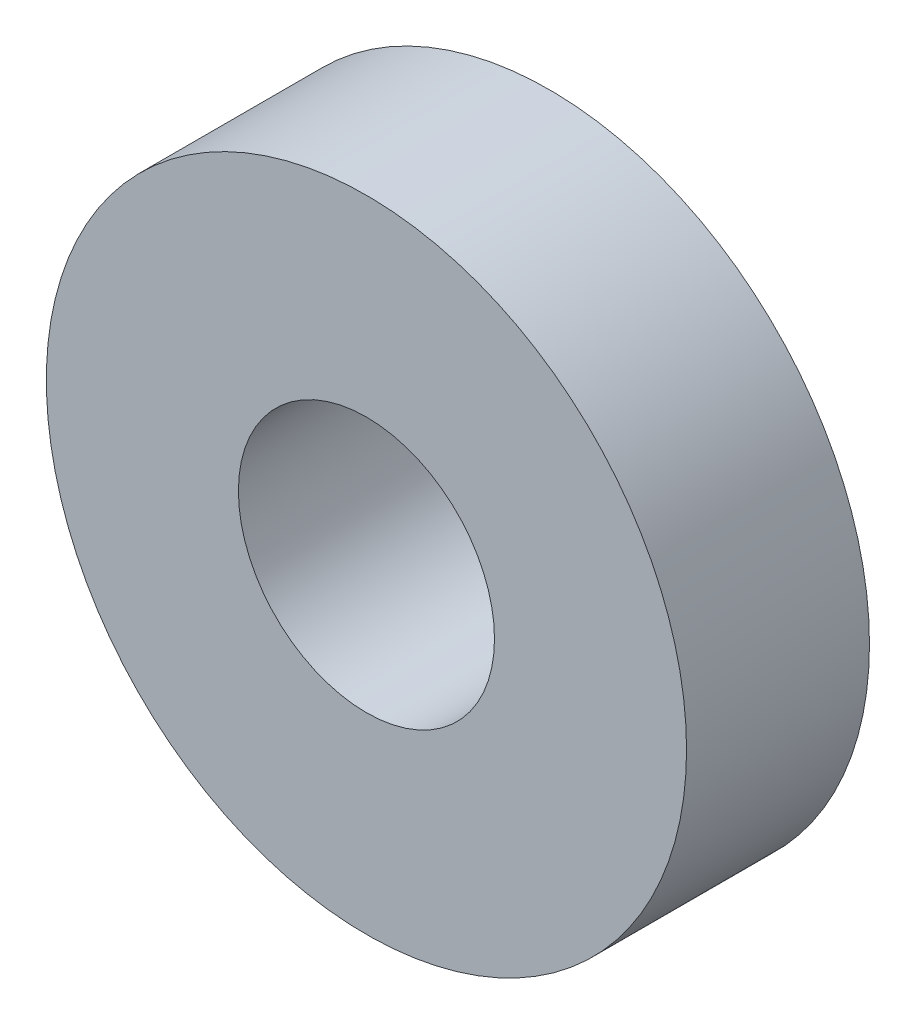
SolidWorks part; units mm, degrees
ref_plane "Plan de face" through (0, 0, 0) normal (0, 0, 1) x (1, 0, 0)
ref_plane "Plan de dessus" through (0, 0, 0) normal (0, 1, 0) x (1, 0, 0)
ref_plane "Plan de droite" through (0, 0, 0) normal (1, 0, 0) x (0, 0, -1)
sketch "Esquisse1" plane through (0, 0, 0) normal (0, 0, 1) x (1, 0, 0)
  circle A0 centre (0, 0) radius 35
  circle A1 centre (0, 0) radius 7
  dimension "D1" = 70
  dimension "D2" = 14
extrude "Boss.-Extru.1" add sketch "Esquisse1" along normal blind 20
sketch "Esquisse2" plane through (0, 0, 0) normal (0, 0, -1) x (-1, 0, 0)
  circle A0 centre (0, 0) radius 14
  dimension "D1" = 28
extrude "Enlèv. mat.-Extru.1" cut sketch "Esquisse2" against normal blind 5
sketch "Esquisse3" plane through (0, 0, 0) normal (0, 0, -1) x (-1, 0, 0)
  line L0 (0, 35) -> (0, -35) construction
  line L1 (-30.3227, 17.4796) -> (30.3227, -17.4796) construction
  line L2 (30.318, 17.4877) -> (-30.318, -17.4877) construction
  circle A0 centre (0, 0) radius 35 construction
  arc A1 (0, 35) -> (-30.3227, 17.4796) centre (0, 0) ccw
  arc A2 (0, 35) -> (30.318, 17.4877) centre (0, 0) cw
  circle A3 centre (-13.589, 22.6021) radius 4
  circle A4 centre (-26.3691, 0.4318) radius 4
  circle A5 centre (26.3691, 0.4318) radius 4
  circle A6 centre (13.589, 22.6021) radius 4
  circle A7 centre (-12.8293, -23.0418) radius 4
  circle A8 centre (12.8416, -23.035) radius 4
  dimension "D1" = 8
extrude "Enlèv. mat.-Extru.3" cut sketch "Esquisse3" against normal blind 5 contours A3 | A6 | A5 | A8 | A7 | A4
sketch "Esquisse8" plane through (0, 0, 0) normal (0, 0, -1) x (-1, 0, 0)
  circle A0 centre (0, 0) radius 14
  dimension "D1" = 28
extrude "Enlèv. mat.-Extru.4" cut sketch "Esquisse8" against normal blind 25
